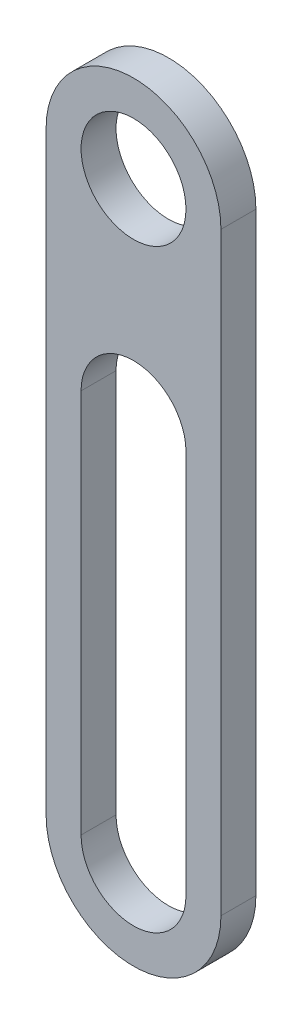
SolidWorks part; units mm, degrees
ref_plane "Front Plane" through (0, 0, 0) normal (0, 0, 1) x (1, 0, 0)
ref_plane "Top Plane" through (0, 0, 0) normal (0, 1, 0) x (1, 0, 0)
ref_plane "Right Plane" through (0, 0, 0) normal (1, 0, 0) x (0, 0, -1)
sketch "Sketch1" plane through (0, 0, 0) normal (0, 0, 1) x (1, 0, 0)
  line L0 (0, -5.5) -> (0, 5.5) construction
  line L1 (-1.5, -5.5) -> (-1.5, 5.5)
  line L2 (1.5, -5.5) -> (1.5, 5.5)
  line L3 (-2.5, 11.5) -> (-2.5, -5.5)
  line L4 (2.5, 11.5) -> (2.5, -5.5)
  arc A0 (-1.5, -5.5) -> (1.5, -5.5) centre (0, -5.5) ccw
  arc A1 (1.5, 5.5) -> (-1.5, 5.5) centre (0, 5.5) ccw
  circle A2 centre (0, 11.5) radius 1.5
  arc A3 (-2.5, 11.5) -> (2.5, 11.5) centre (0, 11.5) cw
  arc A4 (-2.5, -5.5) -> (2.5, -5.5) centre (0, -5.5) ccw
  point P2 (0, 0)
  dimension "D2" = 3
  dimension "D3" = 3
  dimension "D4" = 2.5
  dimension "D1" = 11
  dimension "D5" = 6
extrude "Boss-Extrude1" add sketch "Sketch1" along normal blind 1
